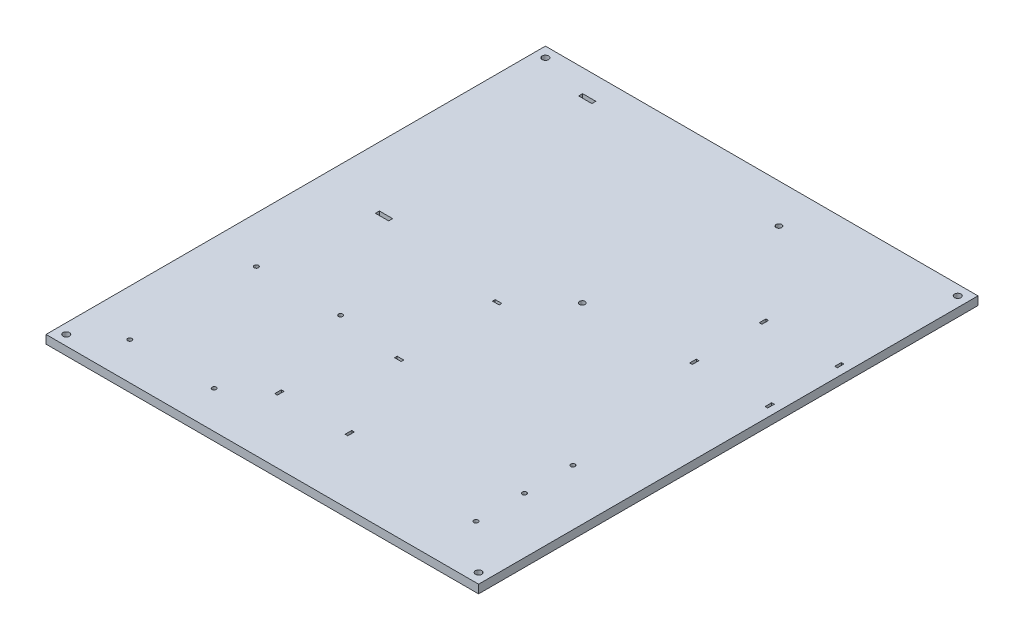
SolidWorks part; units mm, degrees
ref_plane "Front Plane" through (0, 0, 0) normal (0, 0, 1) x (1, 0, 0)
ref_plane "Top Plane" through (0, 0, 0) normal (0, 1, 0) x (1, 0, 0)
ref_plane "Right Plane" through (0, 0, 0) normal (1, 0, 0) x (0, 0, -1)
sketch "Sketch1" plane through (0, 0, 0) normal (0, 1, 0) x (1, 0, 0)
  line L0 (31.75, 126.6) -> (31.75, 25) construction
  line L1 (0, 376) -> (325.7, 376)
  line L2 (0, 376) -> (0, 0)
  line L3 (0, 0) -> (325.7, 0)
  line L4 (325.7, 376) -> (325.7, 0)
  line L5 (155.2, 351) -> (240.7, 351) construction
  line L6 (155.2, 351) -> (155.2, 218) construction
  line L7 (155.2, 218) -> (240.7, 218) construction
  line L8 (240.7, 351) -> (240.7, 218) construction
  line L9 (25.4, 126.6) -> (101.6, 126.6) construction
  line L10 (25.4, 126.6) -> (25.4, 25) construction
  line L11 (25.4, 25) -> (101.6, 25) construction
  line L12 (101.6, 126.6) -> (101.6, 25) construction
  line L13 (264.9, 278.5813) -> (315.7, 278.5813) construction
  line L14 (20, 351) -> (134.5, 351) construction
  line L15 (20, 351) -> (20, 211) construction
  line L16 (20, 211) -> (134.5, 211) construction
  line L17 (134.5, 351) -> (134.5, 211) construction
  line L18 (50, 351) -> (50, 211) construction
  line L19 (271.7, 123) -> (295.7, 123) construction
  line L20 (271.7, 123) -> (271.7, 30) construction
  line L21 (271.7, 30) -> (295.7, 30) construction
  line L22 (295.7, 123) -> (295.7, 30) construction
  line L23 (264.9, 304.775) -> (315.7, 304.775) construction
  line L24 (264.9, 304.775) -> (264.9, 200) construction
  line L25 (264.9, 200) -> (315.7, 200) construction
  line L26 (315.7, 304.775) -> (315.7, 200) construction
  line L27 (45, 206) -> (55, 206)
  line L28 (45, 359) -> (55, 359)
  line L29 (45, 359) -> (45, 356)
  line L30 (45, 356) -> (55, 356)
  line L31 (55, 359) -> (55, 356)
  line L32 (45, 206) -> (45, 203)
  line L33 (45, 203) -> (55, 203)
  line L34 (55, 206) -> (55, 203)
  line L35 (148.88, 187.8) -> (148.88, 120) construction
  line L36 (113.88, 187.8) -> (180.38, 187.8) construction
  line L37 (113.88, 187.8) -> (113.88, 120) construction
  line L38 (113.88, 120) -> (180.38, 120) construction
  line L39 (180.38, 187.8) -> (180.38, 120) construction
  line L40 (146.38, 191.8) -> (151.38, 191.8)
  line L41 (146.38, 118) -> (151.38, 118)
  line L42 (146.38, 118) -> (146.38, 116)
  line L43 (146.38, 116) -> (151.38, 116)
  line L44 (151.38, 118) -> (151.38, 116)
  line L45 (146.38, 191.8) -> (146.38, 189.8)
  line L46 (146.38, 189.8) -> (151.38, 189.8)
  line L47 (151.38, 191.8) -> (151.38, 189.8)
  line L48 (128.7, 50) -> (175.7, 50) construction
  line L49 (128.7, 82) -> (175.7, 82) construction
  line L50 (128.7, 82) -> (128.7, 35) construction
  line L51 (128.7, 35) -> (175.7, 35) construction
  line L52 (175.7, 82) -> (175.7, 35) construction
  line L53 (124.7, 52.5) -> (126.7, 52.5)
  line L54 (177.7, 52.5) -> (179.7, 52.5)
  line L55 (177.7, 52.5) -> (177.7, 47.5)
  line L56 (177.7, 47.5) -> (179.7, 47.5)
  line L57 (179.7, 52.5) -> (179.7, 47.5)
  line L58 (124.7, 52.5) -> (124.7, 47.5)
  line L59 (124.7, 47.5) -> (126.7, 47.5)
  line L60 (126.7, 52.5) -> (126.7, 47.5)
  line L61 (264.9, 226.1937) -> (315.7, 226.1937) construction
  line L62 (317.7, 228.6937) -> (319.7, 228.6937)
  line L63 (317.7, 228.6937) -> (317.7, 223.6937)
  line L64 (317.7, 223.6937) -> (319.7, 223.6937)
  line L65 (319.7, 228.6937) -> (319.7, 223.6937)
  line L66 (260.9, 228.6937) -> (262.9, 228.6937)
  line L67 (260.9, 228.6937) -> (260.9, 223.6937)
  line L68 (260.9, 223.6937) -> (262.9, 223.6938)
  line L69 (262.9, 228.6937) -> (262.9, 223.6938)
  line L70 (317.7, 281.0813) -> (319.7, 281.0813)
  line L71 (317.7, 281.0813) -> (317.7, 276.0813)
  line L72 (317.7, 276.0813) -> (319.7, 276.0813)
  line L73 (319.7, 281.0813) -> (319.7, 276.0813)
  line L74 (260.9, 281.0813) -> (262.9, 281.0813)
  line L75 (260.9, 281.0813) -> (260.9, 276.0813)
  line L76 (260.9, 276.0813) -> (262.9, 276.0813)
  line L77 (262.9, 281.0813) -> (262.9, 276.0813)
  circle A0 centre (7.62, 368.38) radius 2.413
  circle A1 centre (205.238, 346.5828) radius 2.0828
  circle A2 centre (181.362, 222.4172) radius 2.0828
  circle A3 centre (318.08, 368.38) radius 2.413
  circle A4 centre (7.62, 7.62) radius 2.413
  circle A5 centre (318.08, 7.62) radius 2.413
  circle A6 centre (34.925, 123.425) radius 1.5875
  circle A7 centre (98.425, 123.425) radius 1.5875
  circle A8 centre (34.925, 28.1751) radius 1.5875
  circle A9 centre (98.425, 28.1751) radius 1.5875
  circle A10 centre (283.7, 113) radius 1.6256
  circle A11 centre (283.7, 40) radius 1.6256
  circle A12 centre (283.7, 76.5) radius 1.6256
  point P49 (283.7, 30)
  point P50 (283.7, 123)
  point P58 (50, 356)
  point P64 (50, 206)
  point P75 (148.88, 118)
  point P81 (148.88, 189.8)
  point P92 (177.7, 50)
  point P98 (126.7, 50)
  point P107 (317.7, 226.1937)
  point P113 (262.9, 226.1937)
  point P118 (317.7, 278.5813)
  point P124 (262.9, 278.5813)
  dimension "D9" = 4.826
  dimension "D13" = 4.1656
  dimension "D14" = 4.1656
  dimension "D16" = 310.46
  dimension "D22" = 3.175
  dimension "D25" = 63.5
  dimension "D37" = 200
  dimension "D51" = 3.2512
  dimension "D62" = 26.1937
  dimension "D1" = 376
  dimension "D2" = 325.7
  dimension "D5" = 133
  dimension "D6" = 85.5
  dimension "D7" = 7.62
  dimension "D8" = 7.62
  dimension "D10" = 50.038
  dimension "D11" = 26.162
  dimension "D12" = 4.4172
  dimension "D15" = 4.4172
  dimension "D17" = 360.76
  dimension "D18" = 101.6
  dimension "D19" = 76.2
  dimension "D20" = 25.4
  dimension "D21" = 25
  dimension "D23" = 3.175
  dimension "D24" = 3.175
  dimension "D26" = 95.2499
  dimension "D27" = 6.35
  dimension "D28" = 114.5
  dimension "D29" = 140
  dimension "D30" = 20
  dimension "D31" = 25
  dimension "D32" = 24
  dimension "D33" = 30
  dimension "D34" = 93
  dimension "D35" = 30
  dimension "D36" = 30
  dimension "D38" = 10
  dimension "D39" = 10
  dimension "D40" = 10
  dimension "D41" = 3
  dimension "D42" = 5
  dimension "D43" = 10
  dimension "D44" = 3
  dimension "D45" = 5
  dimension "D46" = 66.5
  dimension "D47" = 67.8
  dimension "D48" = 145.32
  dimension "D49" = 120
  dimension "D50" = 35
  dimension "D52" = 46.5
  dimension "D53" = 2
  dimension "D54" = 2
  dimension "D55" = 5
  dimension "D56" = 2
  dimension "D57" = 47
  dimension "D58" = 47
  dimension "D59" = 15
  dimension "D60" = 150
  dimension "D61" = 35
  dimension "D63" = 50.8
  dimension "D64" = 2
  dimension "D65" = 104.775
  dimension "D66" = 26.1937
  dimension "D67" = 2
  dimension "D68" = 25
  dimension "D69" = 10
  dimension "D70" = 2
  dimension "D71" = 2
  dimension "D72" = 2
  dimension "D73" = 2
  dimension "D74" = 85
extrude "Extrude1" add sketch "Sketch1" along normal blind 6.35
